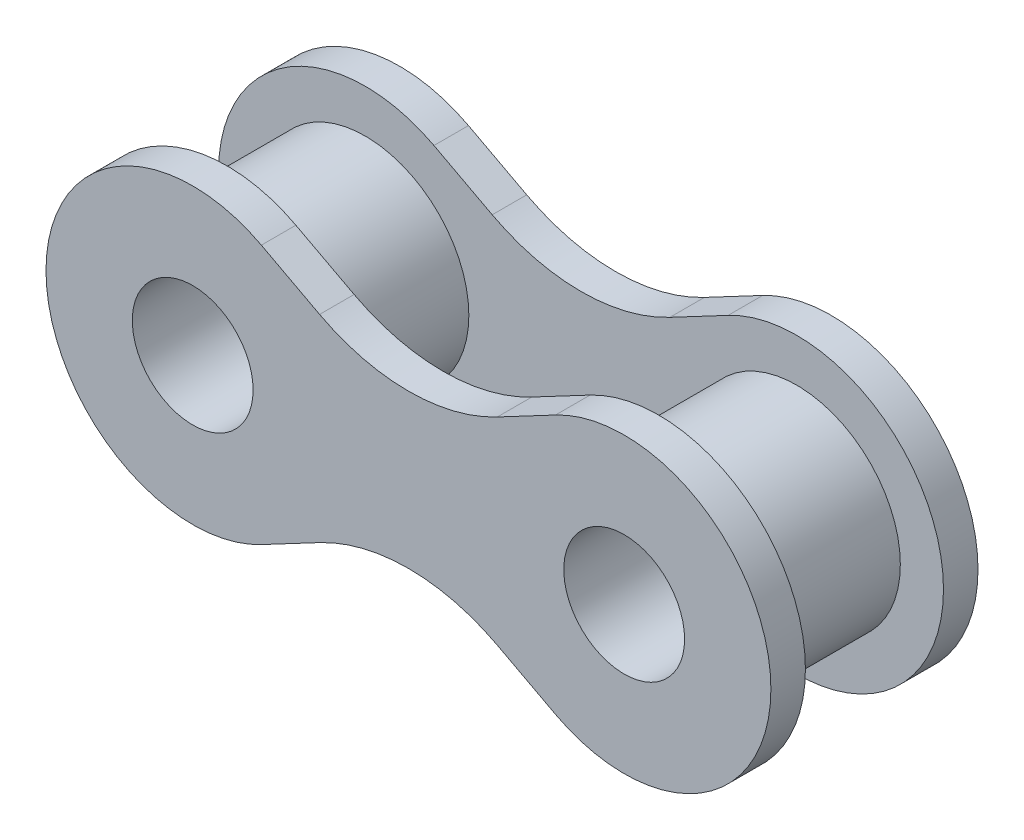
SolidWorks part; units mm, degrees
material "ASTM A36 Steel"
ref_plane "Front Plane" through (0, 0, 0) normal (0, 0, 1) x (1, 0, 0)
ref_plane "Top Plane" through (0, 0, 0) normal (0, 1, 0) x (1, 0, 0)
ref_plane "Right Plane" through (0, 0, 0) normal (1, 0, 0) x (0, 0, -1)
sketch "Sketch1" plane through (0, 0, 0) normal (0, 0, 1) x (1, 0, 0)
  line L0 (0, 0) -> (-6.25, 0) construction
  line L1 (0, 0) -> (6.25, 0) construction
  line L2 (0, 0) -> (0, 1.5) construction
  line L3 (0, 1.5) -> (0, -1.5) construction
  line L4 (-4.2615, 3.7561) -> (-2.5734, 2.8624)
  line L5 (2.5734, 2.8624) -> (4.2615, 3.7561)
  line L6 (-4.2615, -3.7561) -> (-2.5734, -2.8624)
  line L7 (2.5734, -2.8624) -> (4.2615, -3.7561)
  arc A0 (-4.2615, 3.7561) -> (-4.2615, -3.7561) centre (-6.25, 0) ccw
  arc A1 (4.2615, -3.7561) -> (4.2615, 3.7561) centre (6.25, 0) ccw
  circle A2 centre (-6.25, 0) radius 1.75
  circle A3 centre (6.25, 0) radius 1.75
  arc A4 (-2.5734, -2.8624) -> (2.5734, -2.8624) centre (0, -7.7232) cw
  arc A5 (-2.5734, 2.8624) -> (2.5734, 2.8624) centre (0, 7.7232) ccw
  dimension "D3" = 8.5
  dimension "D4" = 8.5
  dimension "D5" = 3.5
  dimension "D6" = 3.5
  dimension "D8" = 5.5
  dimension "D1" = 6.25
  dimension "D2" = 6.25
  dimension "D7" = 1.5
extrude "Boss-Extrude1" add sketch "Sketch1" along normal mid plane 1
ref_plane "Plane1" through (0, 0, 5.5) normal (0, 0, 1) x (1, 0, 0)
sketch "Sketch2" plane through (0, 0, 5.5) normal (0, 0, 1) x (1, 0, 0)
  line L4 (-2.5734, 2.8624) -> (-4.2615, 3.7561)
  line L5 (-4.2615, -3.7561) -> (-2.5734, -2.8624)
  line L6 (2.5734, -2.8624) -> (4.2615, -3.7561)
  line L7 (4.2615, 3.7561) -> (2.5734, 2.8624)
  line L8 (-2.5734, 2.8624) -> (-4.2615, 3.7561)
  line L9 (-4.2615, -3.7561) -> (-2.5734, -2.8624)
  line L10 (2.5734, -2.8624) -> (4.2615, -3.7561)
  line L11 (4.2615, 3.7561) -> (2.5734, 2.8624)
  circle A1 centre (6.25, 0) radius 1.75
  circle A2 centre (6.25, 0) radius 1.75
  circle A3 centre (-6.25, 0) radius 1.75
  circle A4 centre (-6.25, 0) radius 1.75
  arc A8 (-4.2615, 3.7561) -> (-4.2615, -3.7561) centre (-6.25, 0) ccw
  arc A9 (2.5734, -2.8624) -> (-2.5734, -2.8624) centre (0, -7.7232) ccw
  arc A10 (4.2615, -3.7561) -> (4.2615, 3.7561) centre (6.25, 0) ccw
  arc A11 (-2.5734, 2.8624) -> (2.5734, 2.8624) centre (0, 7.7232) ccw
  arc A12 (-4.2615, 3.7561) -> (-4.2615, -3.7561) centre (-6.25, 0) ccw
  arc A13 (2.5734, -2.8624) -> (-2.5734, -2.8624) centre (0, -7.7232) ccw
  arc A14 (4.2615, -3.7561) -> (4.2615, 3.7561) centre (6.25, 0) ccw
  arc A15 (-2.5734, 2.8624) -> (2.5734, 2.8624) centre (0, 7.7232) ccw
  dimension "D1" = 0
  dimension "D2" = 0
  dimension "D3" = 0
extrude "Boss-Extrude2" add sketch "Sketch2" against normal blind 1 separate body
sketch "Sketch3" plane through (0, 0, 5.5) normal (0, 0, 1) x (1, 0, 0)
  circle A0 centre (-6.25, 0) radius 1.75 construction
  circle A1 centre (-6.25, 0) radius 1.75
  circle A2 centre (-6.25, 0) radius 3
  circle A3 centre (6.25, 0) radius 1.75 construction
  circle A4 centre (6.25, 0) radius 1.75
  circle A5 centre (6.25, 0) radius 3
  dimension "D1" = 6
  dimension "D2" = 6
extrude "Boss-Extrude3" add sketch "Sketch3" against normal up to surface (6 mm away) up to face at (-4.5, 0, -0.5)
ref_plane "MID PLANE" through (0, 0, 2.5) normal (0, 0, 1) x (1, 0, 0)
